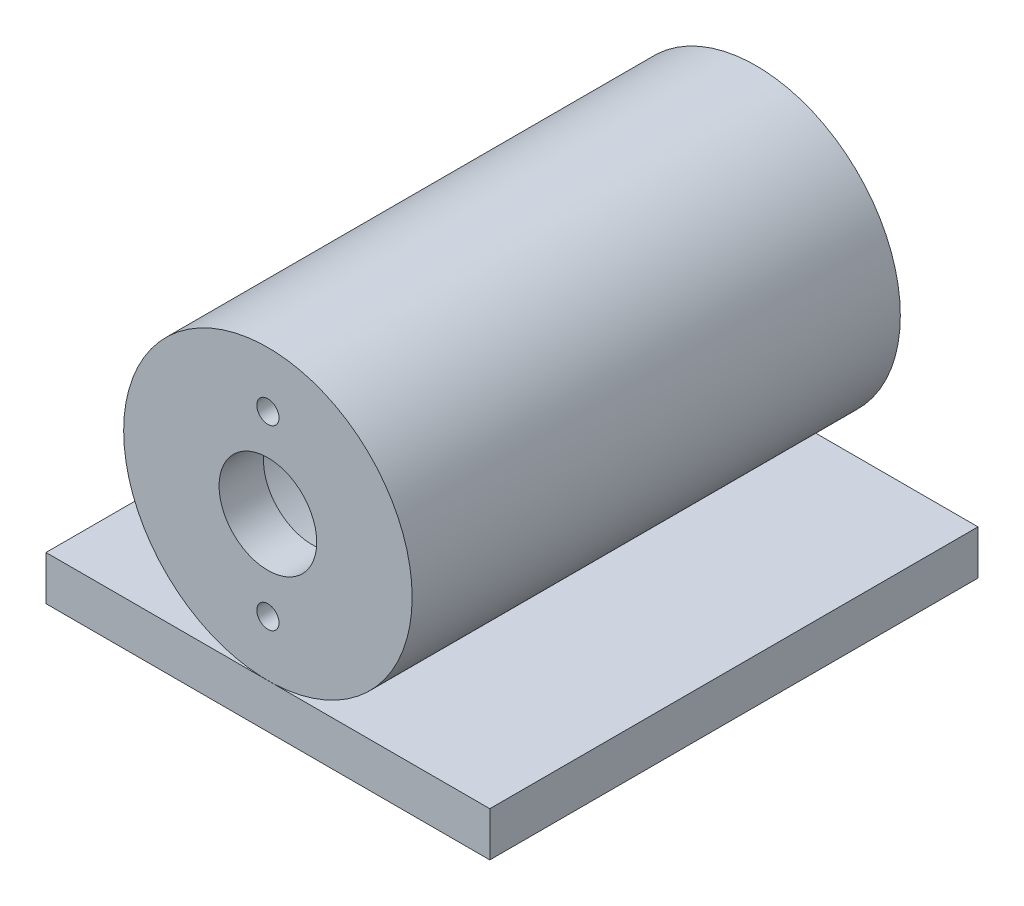
SolidWorks part; units mm, degrees
ref_plane "Front Plane" through (0, 0, 0) normal (0, 0, 1) x (1, 0, 0)
ref_plane "Top Plane" through (0, 0, 0) normal (0, 1, 0) x (1, 0, 0)
ref_plane "Right Plane" through (0, 0, 0) normal (1, 0, 0) x (0, 0, -1)
sketch "Sketch1" plane through (0, 0, 0) normal (0, 0, 1) x (1, 0, 0)
  circle A0 centre (0, 0) radius 6.985
  circle A1 centre (0, 0) radius 19.05
  circle A2 centre (0, 0) radius 12.7 construction
  circle A3 centre (0, 12.7) radius 1.5875
  circle A4 centre (0, -12.7) radius 1.5875
  circle A5 centre (0, 0) radius 20.6375
  dimension "D1" = 38.1
  dimension "D2" = 13.97
  dimension "D3" = 25.4
  dimension "D4" = 3.175
  dimension "D5" = 41.275
extrude "Boss-Extrude1" add sketch "Sketch1" along normal blind 6.35 contours A5 A1 | A1 A4 A3 A0
sketch "Sketch2" plane through (0, 0, 0) normal (0, 0, -1) x (-1, 0, 0)
  circle A0 centre (0, 0) radius 20.6375
  circle A1 centre (0, 0) radius 17.4625
  dimension "D1" = 3.175
extrude "Boss-Extrude2" add sketch "Sketch2" along normal blind 63.5
sketch3d "3DSketch2"
  line L0 (0, -20.6375, 6.35) -> (0, -20.6375, -63.5) construction
  line L1 (-31.75, -20.6375, 6.35) -> (31.75, -20.6375, 6.35)
  line L2 (-31.75, -20.6375, 6.35) -> (-31.75, -20.6375, -63.5)
  line L3 (-31.75, -20.6375, -63.5) -> (31.75, -20.6375, -63.5)
  line L4 (31.75, -20.6375, 6.35) -> (31.75, -20.6375, -63.5)
  circle A0 centre (0, 0, 6.35) radius 20.6375 construction
  circle A1 centre (0, 0, -63.5) radius 20.6375 construction
  point P6 (0, 0, 26.9875)
  point P9 (0, 0, -84.1375)
  dimension "D1" = 63.5
extrude "Boss-Extrude3" add sketch "3DSketch2" along a picked direction on the side of the normal blind 6.35 separate body
